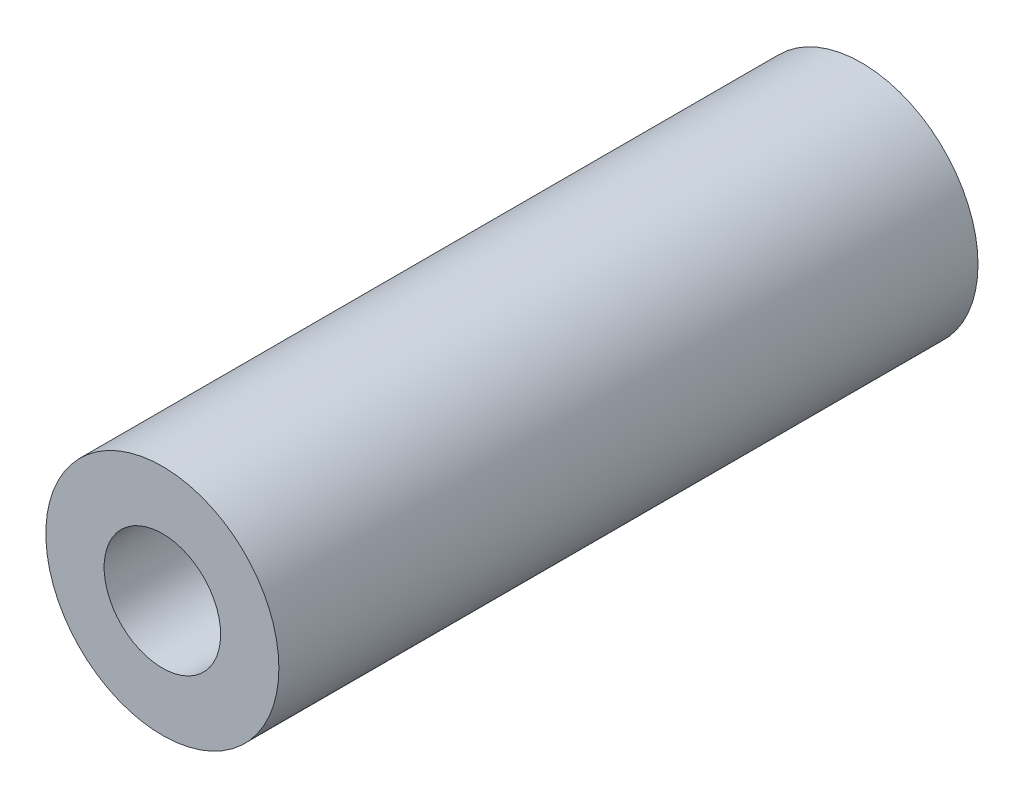
SolidWorks part; units mm, degrees
ref_plane "Front Plane" through (0, 0, 0) normal (0, 0, 1) x (1, 0, 0)
ref_plane "Top Plane" through (0, 0, 0) normal (0, 1, 0) x (1, 0, 0)
ref_plane "Right Plane" through (0, 0, 0) normal (1, 0, 0) x (0, 0, -1)
sketch "Sketch1" plane through (0, 0, 0) normal (0, 0, 1) x (1, 0, 0)
  circle A0 centre (-32.5, 171.4711) radius 1.25
  circle A1 centre (-32.5, 171.4711) radius 2.5
  point P5 (-32.5, 171.4711)
  point P6 (-32.5, 171.3208)
  dimension "D1" = 2.5
  dimension "D2" = 5
extrude "Boss-Extrude1" add sketch "Sketch1" along normal blind 15
